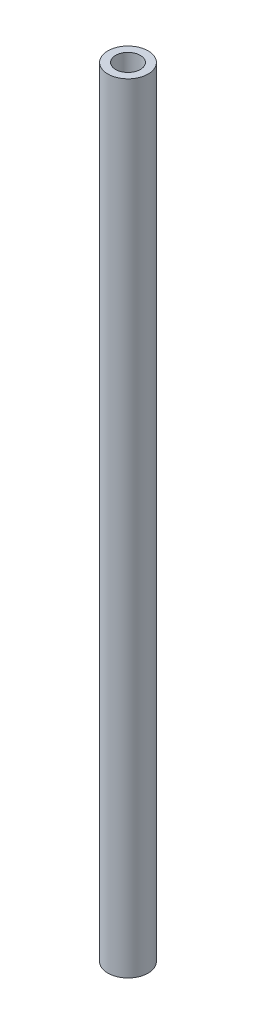
SolidWorks part; units mm, degrees
ref_plane "Front Plane" through (0, 0, 0) normal (0, 0, 1) x (1, 0, 0)
ref_plane "Top Plane" through (0, 0, 0) normal (0, 1, 0) x (1, 0, 0)
ref_plane "Right Plane" through (0, 0, 0) normal (1, 0, 0) x (0, 0, -1)
sketch "Sketch1" plane through (0, 0, 0) normal (0, 1, 0) x (1, 0, 0)
  circle A0 centre (0, 0) radius 1.55
  circle A1 centre (0, 0) radius 0.95
  dimension "D1" = 3.1
  dimension "D2" = 1.9
extrude "Boss-Extrude1" add sketch "Sketch1" along normal blind 60
